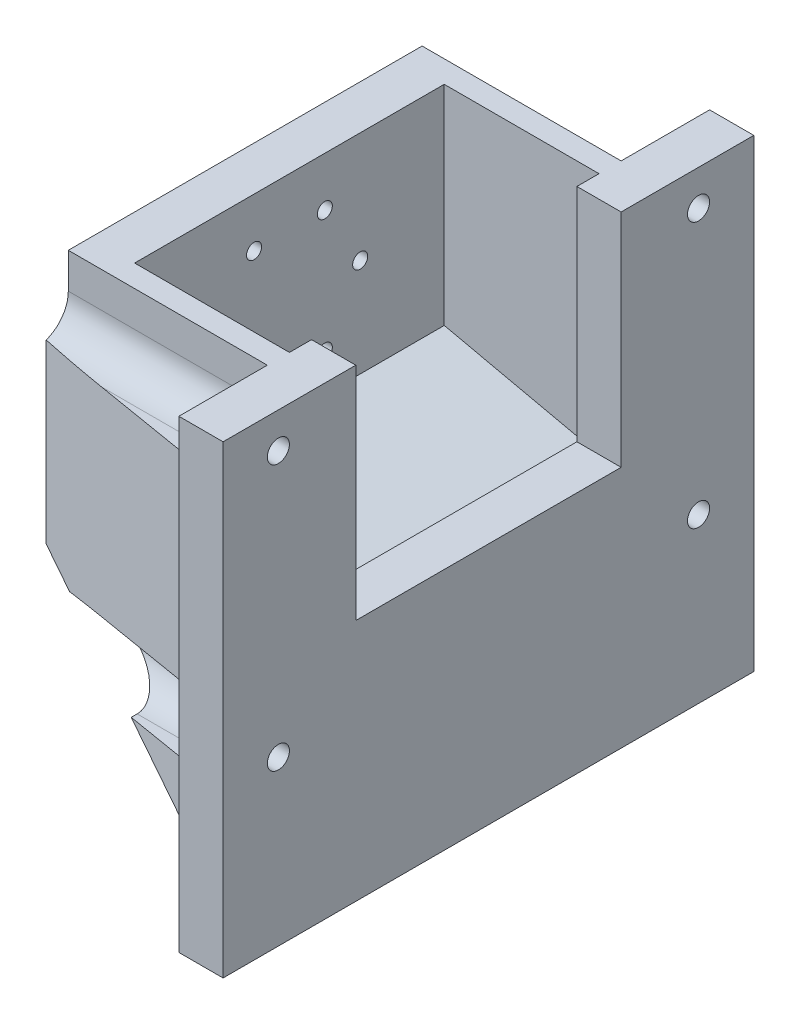
SolidWorks part; units mm, degrees
material "ABS"
ref_plane "Front" through (0, 0, 0) normal (0, 0, 1) x (1, 0, 0)
ref_plane "Top" through (0, 0, 0) normal (0, 1, 0) x (1, 0, 0)
ref_plane "Right" through (0, 0, 0) normal (1, 0, 0) x (0, 0, -1)
sketch "Croquis1" plane through (0, 0, 0) normal (1, 0, 0) x (0, 0, -1)
  line L0 (0, 50) -> (0, -50) construction
  line L2 (-60, -52.5) -> (-60, 52.5)
  line L3 (-60, 52.5) -> (60, 52.5)
  line L4 (60, -52.5) -> (60, 52.5)
  line L5 (-60, -52.5) -> (60, 52.5) construction
  line L6 (-60, 52.5) -> (60, -52.5) construction
  line L7 (-47.5, -15.5) -> (47.5, -15.5) construction
  line L8 (-47.5, -15.5) -> (-47.5, 44.5) construction
  line L9 (-47.5, 44.5) -> (47.5, 44.5) construction
  line L10 (47.5, -15.5) -> (47.5, 44.5) construction
  line L11 (-47.5, -15.5) -> (47.5, 44.5) construction
  line L12 (-47.5, 44.5) -> (47.5, -15.5) construction
  line L13 (30, 52.5) -> (-30, 52.5)
  line L14 (30, 52.5) -> (30, 2.5)
  line L15 (30, 2.5) -> (-30, 2.5)
  line L16 (-30, 52.5) -> (-30, 2.5)
  line L23 (-60, -52.5) -> (60, -52.5)
  circle A4 centre (47.5, 44.5) radius 2.5
  circle A5 centre (-47.5, 44.5) radius 2.5
  circle A6 centre (-47.5, -15.5) radius 2.5
  circle A7 centre (47.5, -15.5) radius 2.5
  point P0 (0, 0)
  point P6 (0, 0)
  point P15 (0, 2.5)
  point P18 (0, -50)
  point P38 (0, 14.5)
  dimension "D10" = 5
  dimension "D1" = 120
  dimension "D2" = 105
  dimension "D3" = 95
  dimension "D4" = 60
  dimension "D5" = 60
  dimension "D9" = 50
  dimension "D11" = 8
extrude "Saliente-Extruir1" add sketch "Croquis1" along normal mid plane 10
sketch "Croquis7" plane through (-5, 0, 0) normal (-1, 0, 0) x (0, 0, 1)
  line L0 (0, -30.2501) -> (0, 30.2501) construction
  line L1 (-52.5, -42.5) -> (52.5, -42.5)
  line L2 (-52.5, -42.5) -> (-52.5, 52.5)
  line L3 (-52.5, 52.5) -> (-35, 52.5)
  line L4 (52.5, -42.5) -> (52.5, 52.5)
  line L5 (-52.5, -42.5) -> (52.5, 52.5) construction
  line L6 (-52.5, 52.5) -> (52.5, -42.5) construction
  line L7 (60, 52.5) -> (30, 52.5) construction
  line L8 (-35, 52.5) -> (-35, -2.5)
  line L9 (-35, -2.5) -> (35, -2.5)
  line L10 (35, -2.5) -> (35, 52.5)
  line L11 (35, 52.5) -> (52.5, 52.5)
  point P0 (0, 5)
  point P13 (0, -2.5)
  dimension "D1" = 95
  dimension "D2" = 105
  dimension "D3" = 55
  dimension "D4" = 70
ref_plane "Plano1" through (-50, 0, 0) normal (1, 0, 0) x (0, 0, -1)
sketch "Croquis8" plane through (-50, 0, 0) normal (1, 0, 0) x (0, 0, -1)
  line L0 (0, 30.2501) -> (0, -30.2501) construction
  line L1 (-45, -2.5) -> (45, -2.5)
  line L2 (-45, -2.5) -> (-45, 52.5)
  line L3 (-45, 52.5) -> (-35, 52.5)
  line L4 (45, -2.5) -> (45, 52.5)
  line L5 (-45, -2.5) -> (45, 52.5) construction
  line L6 (-45, 52.5) -> (45, -2.5) construction
  line L7 (30, 52.5) -> (60, 52.5) construction
  line L8 (-35, 52.5) -> (-35, 7.5)
  line L9 (-35, -2.5) -> (-35, 52.5) construction
  line L10 (-35, 7.5) -> (35, 7.5)
  line L11 (35, 52.5) -> (35, -2.5) construction
  line L12 (35, 7.5) -> (35, 52.5)
  line L13 (35, 52.5) -> (45, 52.5)
  point P0 (0, 25)
  dimension "D1" = 55
  dimension "D2" = 90
  dimension "D3" = 45
loft "Recubrir3" add profiles "Croquis7", "Croquis8"
sketch "Croquis9" plane through (-50, 0, 0) normal (-1, 0, 0) x (0, 0, 1)
  line L1 (-45, 52.5) -> (45, 52.5)
  line L2 (-45, 52.5) -> (-45, -2.5)
  line L3 (-45, -2.5) -> (45, -2.5)
  line L4 (45, 52.5) -> (45, -2.5)
extrude "Saliente-Extruir2" add sketch "Croquis9" against normal blind 10
hole_wizard "Refrentado para tornillo con cabeza troncocónica de M34" positions "Croquis10" profile "Croquis11" counterbore size "M3" standard "Ansi Metric" end condition up to next
sketch "Croquis10" plane through (-50, 0, 0) normal (-1, 0, 0) x (0, 0, 1)
  line L2 (-8, 41.3564) -> (0, 27.5) construction
  line L3 (0, -30.2501) -> (0, 30.2501) construction
  line L6 (-45, 52.5) -> (45, 52.5) construction
  point P0 (-8, 41.3564)
  point P23 (8, 41.3564)
  point P24 (16, 27.5)
  point P25 (8, 13.6436)
  point P26 (-8, 13.6436)
  point P27 (-16, 27.5)
  point P29 (-99.109, 35.5572)
  dimension "D1" = 16
  dimension "D2" = 25
  dimension "D3" = 30
  dimension "D4" = 6
sketch "Croquis11" plane through (-50, 41.3564, -8) normal (0, 1, 0) x (0, 0, 1)
  line L0 (0, 0) -> (0, 10)
  line L1 (0, 10) -> (1.7, 10)
  line L3 (1.7, 10) -> (1.7, 2.4)
  line L4 (1.7, 2.4) -> (3.5, 2.4)
  line L5 (3.5, 2.4) -> (3.5, 0)
  line L7 (3.5, 0) -> (0, 0)
  line L11 (0, -6.35) -> (0, 107.95) construction
  dimension "Diámetro de taladro hasta el siguiente" = 3.4
  dimension "Profundidad de taladro hasta el siguiente" = 10
  dimension "Diámetro de refrentado" = 7
  dimension "Profundidad de refrentado" = 2.4
sketch "Croquis12" plane through (-50, 0, 0) normal (-1, 0, 0) x (0, 0, 1)
  line L0 (0, -30.2501) -> (0, 30.2501) construction
  line L1 (-47.5, -15.5) -> (47.5, -15.5) construction
  line L2 (-47.5, -15.5) -> (-47.5, 44.5) construction
  line L3 (-47.5, 44.5) -> (47.5, 44.5) construction
  line L4 (47.5, -15.5) -> (47.5, 44.5) construction
  line L5 (-47.5, -15.5) -> (47.5, 44.5) construction
  line L6 (-47.5, 44.5) -> (47.5, -15.5) construction
  line L7 (-45, 52.5) -> (45, 52.5) construction
  line L8 (-40, 44.5) -> (-40, 52.5)
  line L9 (-40, 52.5) -> (-55, 52.5)
  line L10 (-52.5, 52.5) -> (-60, 52.5) construction
  line L11 (-55, 52.5) -> (-55, 44.5)
  line L12 (-47.5, 37) -> (-55, 37)
  line L13 (-55, 37) -> (-55, 44.5)
  line L14 (40, 44.5) -> (40, 52.5)
  line L15 (40, 52.5) -> (55, 52.5)
  line L16 (60, 52.5) -> (52.5, 52.5) construction
  line L17 (55, 52.5) -> (55, 44.5)
  line L18 (55, 44.5) -> (55, 37)
  line L19 (55, 37) -> (47.5, 37)
  line L20 (47.5, -8) -> (55, -8)
  line L21 (55, -8) -> (55, -15.5)
  line L22 (55, -15.5) -> (55, -23)
  line L23 (55, -23) -> (47.5, -23)
  line L24 (-47.5, -8) -> (-55, -8)
  line L25 (-55, -8) -> (-55, -15.5)
  line L26 (-55, -15.5) -> (-55, -23)
  line L27 (-55, -23) -> (-47.5, -23)
  arc A0 (-47.5, 37) -> (-40, 44.5) centre (-47.5, 44.5) ccw
  arc A2 (40, 44.5) -> (47.5, 37) centre (47.5, 44.5) ccw
  arc A3 (47.5, -8) -> (47.5, -23) centre (47.5, -15.5) ccw
  arc A4 (-47.5, -23) -> (-47.5, -8) centre (-47.5, -15.5) ccw
  point P0 (0, 14.5)
  point P11 (-55, -8.7521)
  dimension "D4" = 15
  dimension "D1" = 95
  dimension "D2" = 60
  dimension "D3" = 8
extrude "Cortar-Extruir1" cut sketch "Croquis12" against normal up to surface (45 mm away) up to face at (-5, 2.5, -5.625)
